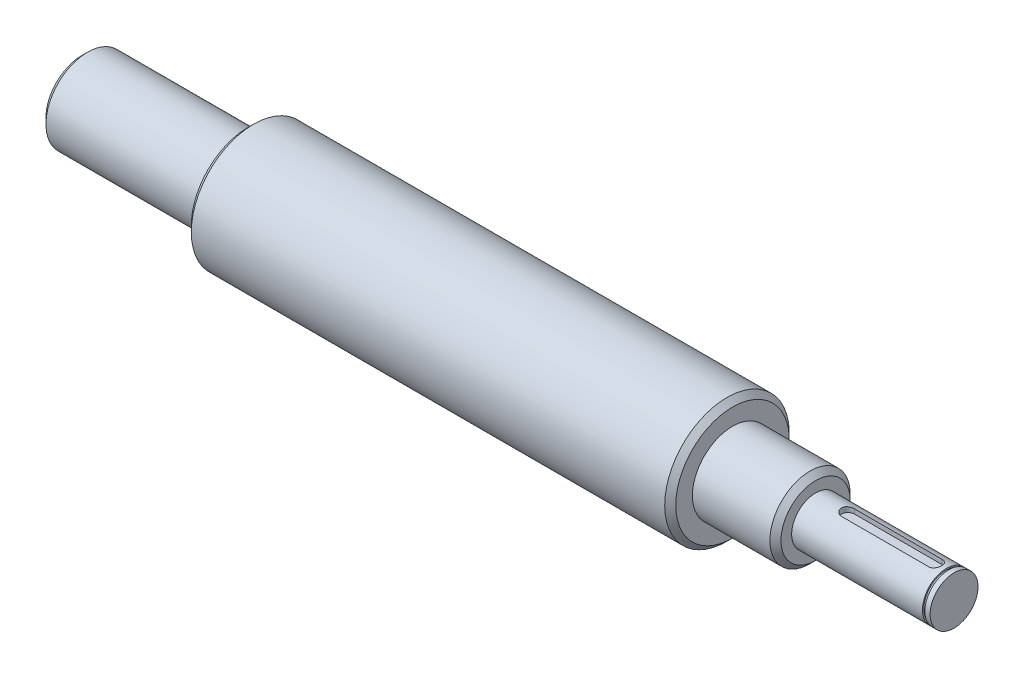
SolidWorks part; units mm, degrees
ref_plane "Front Plane" through (0, 0, 0) normal (0, 0, 1) x (1, 0, 0)
ref_plane "Top Plane" through (0, 0, 0) normal (0, 1, 0) x (1, 0, 0)
ref_plane "Right Plane" through (0, 0, 0) normal (1, 0, 0) x (0, 0, -1)
sketch "Sketch1" plane through (0, 0, 0) normal (0, 0, 1) x (1, 0, 0)
  line L0 (-1910.9611, 0) -> (93637.0942, 0) construction
  line L1 (-200, 0) -> (200, 0)
  line L2 (-200, 0) -> (-200, 19.05)
  line L3 (-200, 19.05) -> (-123.8, 19.05)
  line L4 (-123.8, 19.05) -> (-123.8, 28.575)
  line L5 (-123.8, 28.575) -> (98.4, 28.575)
  line L6 (98.4, 28.575) -> (98.4, 18.415)
  line L7 (98.4, 18.415) -> (136.5, 18.415)
  line L8 (136.5, 18.415) -> (136.5, 11)
  line L9 (136.5, 11) -> (200, 11)
  line L10 (200, 11) -> (200, 0)
  point P5 (0, 0)
  dimension "D1" = 400
  dimension "D2" = 38.1
  dimension "D3" = 76.2
  dimension "D4" = 57.15
  dimension "D5" = 38.1
  dimension "D6" = 36.83
  dimension "D7" = 22
  dimension "D8" = 63.5
revolve "Revolve1" add sketch "Sketch1" angle 360 about L0
chamfer "Chamfer1" distance 2.54 angle 45 2 edges at (136.5, 0, 18.415) (98.4, 0, 28.575)
chamfer "Chamfer2" distance 2.54 angle 45 2 edges at (-123.8, 0, 28.575) (-200, 0, 19.05)
fillet "Fillet1" radius 2.54 1 edges at (-123.8, 0, 19.05)
ref_plane "Plane2" through (0, 11, 0) normal (0, 1, 0) x (1, 0, 0)
sketch "Sketch3" plane through (0, 11, 0) normal (0, 1, 0) x (1, 0, 0)
  line L0 (141.375, 0) -> (151.375, 0) construction
  line L1 (141.375, -11) -> (141.375, 11) construction
  line L2 (151.375, 0) -> (191.375, 0) construction
  line L3 (151.375, 3) -> (191.375, 3)
  line L4 (151.375, -3) -> (191.375, -3)
  arc A0 (151.375, 3) -> (151.375, -3) centre (151.375, 0) ccw
  arc A1 (191.375, -3) -> (191.375, 3) centre (191.375, 0) ccw
  point P5 (171.375, 0)
  dimension "D1" = 10
  dimension "D2" = 40
  dimension "D3" = 6
extrude "Cut-Extrude2" cut sketch "Sketch3" against normal blind 2.5
ref_plane "Plane3" through (196.4977, 0, 0) normal (1, 0, 0) x (0, 0, -1)
sketch "Sketch7" plane through (196.4977, 0, 0) normal (1, 0, 0) x (0, 0, -1)
  circle A0 centre (0, 0) radius 10.35
  circle A1 centre (0, 0) radius 11
  dimension "D1" = 20.7
extrude "Cut-Extrude3" cut sketch "Sketch7" along normal blind 1.1
equation "\"D5@Sketch1\"=\"D3@Sketch1\"/2"
